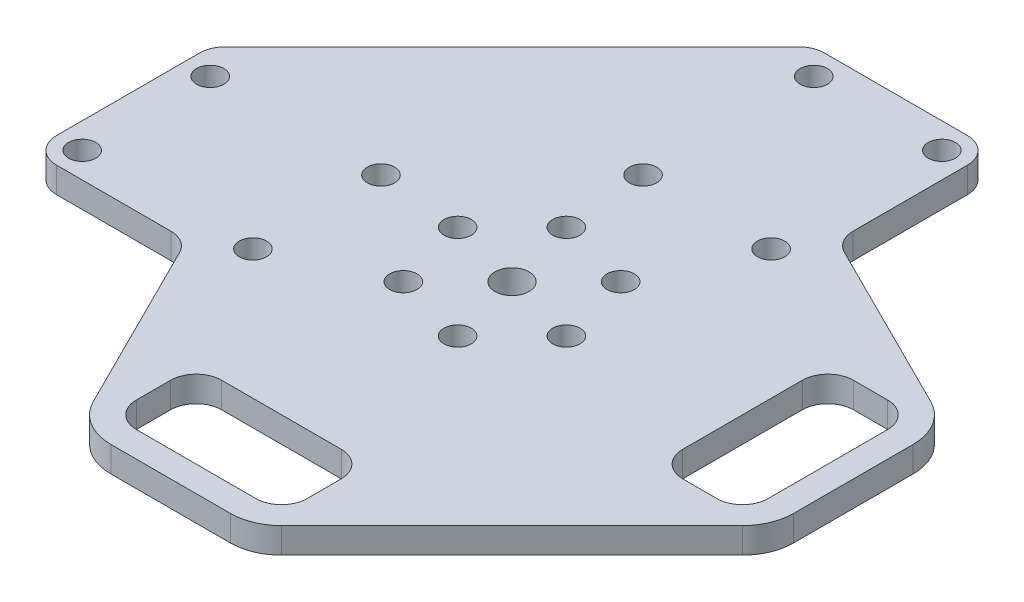
SolidWorks part; units mm, degrees
material "6061-T6 (SS)"
ref_plane "Front Plane" through (0, 0, 0) normal (0, 0, 1) x (1, 0, 0)
ref_plane "Top Plane" through (0, 0, 0) normal (0, 1, 0) x (1, 0, 0)
ref_plane "Right Plane" through (0, 0, 0) normal (1, 0, 0) x (0, 0, -1)
sketch "Sketch1" plane through (0, 0, 0) normal (0, 1, 0) x (1, 0, 0)
  line L1 (11.85, 18.5) -> (-3.15, 18.5)
  line L2 (11.85, 18.5) -> (11.85, 38.5)
  line L3 (11.85, 38.5) -> (-3.15, 38.5)
  line L4 (-3.15, 18.5) -> (-3.15, 38.5)
  line L5 (11.85, 18.5) -> (-3.15, 38.5) construction
  line L6 (11.85, 38.5) -> (-3.15, 18.5) construction
  line L7 (-18.5, -11.85) -> (-38.5, -11.85)
  line L8 (-18.5, -11.85) -> (-18.5, 3.15)
  line L9 (-18.5, 3.15) -> (-38.5, 3.15)
  line L10 (-38.5, -11.85) -> (-38.5, 3.15)
  line L11 (-18.5, -11.85) -> (-38.5, 3.15) construction
  line L12 (-18.5, 3.15) -> (-38.5, -11.85) construction
  line L13 (21.7, 15) -> (-13, 15)
  line L14 (21.7, 15) -> (21.7, 42)
  line L15 (21.7, 42) -> (-13, 42)
  line L16 (-13, 15) -> (-13, 42)
  line L17 (21.7, 15) -> (-13, 42) construction
  line L18 (21.7, 42) -> (-13, 15) construction
  line L19 (-15, -21.7) -> (-42, -21.7)
  line L20 (-15, -21.7) -> (-15, 13)
  line L21 (-15, 13) -> (-42, 13)
  line L22 (-42, -21.7) -> (-42, 13)
  line L23 (-15, -21.7) -> (-42, 13) construction
  line L24 (-15, 13) -> (-42, -21.7) construction
  circle A0 centre (0, 0) radius 2
  circle A1 centre (0, 0) radius 9
  circle A2 centre (0, 0) radius 12.7
  point P3 (4.35, 28.5)
  point P8 (-28.5, -4.35)
  point P16 (-28.5, -4.35)
  point P17 (4.35, 28.5)
  dimension "D1" = 4
  dimension "D4" = 18
  dimension "D11" = 25.4
  dimension "D2" = 20
  dimension "D3" = 15
  dimension "D5" = 34.7
  dimension "D6" = 27
  dimension "D7" = 2
  dimension "D8" = 2
  dimension "D9" = 15
  dimension "D10" = 15
sketch "Sketch2" plane through (0, 0, 0) normal (0, 1, 0) x (1, 0, 0)
  line L0 (-6.15, 41.5) -> (14.85, 41.5)
  line L1 (14.85, 41.5) -> (14.85, 15.5)
  line L3 (-15.5, -14.85) -> (-41.5, -14.85)
  line L4 (-41.5, -14.85) -> (-41.5, 6.15)
  line L5 (-41.5, 6.15) -> (-6.15, 41.5)
  line L6 (-18.5, -11.85) -> (-38.5, -11.85) construction
  line L7 (11.85, 18.5) -> (11.85, 38.5) construction
  line L8 (11.85, 38.5) -> (-3.15, 38.5) construction
  line L9 (-38.5, -11.85) -> (-38.5, 3.15) construction
  line L10 (-18.5, -11.85) -> (-18.5, 3.15) construction
  line L11 (11.85, 18.5) -> (-3.15, 18.5) construction
  line L12 (-18.5, 3.15) -> (-38.5, 3.15) construction
  line L13 (-3.15, 18.5) -> (-3.15, 38.5) construction
  line L14 (-15.5, -14.85) -> (0.9826, -13.6647)
  line L15 (14.85, 15.5) -> (13.6647, -0.9826)
  circle A1 centre (0, 0) radius 12.7 construction
  arc A3 (0.9826, -13.6647) -> (13.6647, -0.9826) centre (0, 0) ccw
  point P11 (0, 0)
  dimension "D1" = 1
  dimension "D2" = 3
  dimension "D3" = 3
  dimension "D4" = 3
  dimension "D5" = 3
  dimension "D6" = 3
  dimension "D7" = 3
  dimension "D8" = 3
  dimension "D9" = 3
extrude "Boss-Extrude1" add sketch "Sketch2" along normal blind 3
hole_wizard "M3 Clearance Hole1" positions "Sketch3" profile "Sketch4" hole size "M3" standard "ANSI Metric" end condition up to next
sketch "Sketch3" plane through (0, 3, 0) normal (0, 1, 0) x (1, 0, 0)
  point P0 (-38.5, 3.15)
  point P3 (-18.5, 3.15)
  point P6 (-18.5, -11.85)
  point P9 (-38.5, -11.85)
  point P12 (-3.15, 18.5)
  point P15 (-3.15, 38.5)
  point P18 (11.85, 38.5)
  point P21 (11.85, 18.5)
sketch "Sketch4" plane through (-38.5, 3, -3.15) normal (1, 0, 0) x (0, 0, 1)
  line L0 (0, 0) -> (0, 3)
  line L1 (0, 3) -> (1.6, 3)
  line L2 (1.6, 3) -> (1.6, 0)
  line L5 (1.6, 0) -> (0, 0)
  line L11 (0, -6.35) -> (0, 107.95) construction
  dimension "Thru Hole Dia." = 3.2
  dimension "Thru Hole Depth" = 3
hole_wizard "M3 Clearance Hole2" positions "Sketch5" profile "Sketch6" hole size "M3" standard "ANSI Metric" end condition up to next
sketch "Sketch5" plane through (0, 3, 0) normal (0, 1, 0) x (1, 0, 0)
  line L4 (-8.6933, 2.3294) -> (-2.3294, 8.6933) construction
  line L5 (0, 0) -> (-5.5114, 5.5114) construction
  line L7 (-1000, 0) -> (49000, 0) construction
  circle A0 centre (0, 0) radius 9 construction
  point P23 (-2.3294, 8.6933)
  point P46 (6.364, 6.364)
  point P47 (8.6933, -2.3294)
  point P48 (2.3294, -8.6933)
  point P49 (-6.364, -6.364)
  point P50 (-8.6933, 2.3294)
  dimension "D1" = 45
  dimension "D2" = 6
sketch "Sketch6" plane through (-2.3294, 3, -8.6933) normal (1, 0, 0) x (0, 0, 1)
  line L0 (0, 0) -> (0, 3)
  line L1 (0, 3) -> (1.6, 3)
  line L2 (1.6, 3) -> (1.6, 0)
  line L5 (1.6, 0) -> (0, 0)
  line L11 (0, -6.35) -> (0, 107.95) construction
  dimension "Thru Hole Dia." = 3.2
  dimension "Thru Hole Depth" = 3
hole_wizard "Ø4.0 (4) Diameter Hole1" positions "Sketch7" profile "Sketch8" hole size "Ø4.0" standard "ANSI Metric" end condition up to next
sketch "Sketch7" plane through (0, 3, 0) normal (0, 1, 0) x (1, 0, 0)
  point P0 (0, 0)
sketch "Sketch8" plane through (0, 3, 0) normal (1, 0, 0) x (0, 0, 1)
  line L0 (0, 0) -> (0, 3)
  line L1 (0, 3) -> (2, 3)
  line L2 (2, 3) -> (2, 0)
  line L5 (2, 0) -> (0, 0)
  line L11 (0, -6.35) -> (0, 107.95) construction
  dimension "Thru Hole Dia." = 4
  dimension "Thru Hole Depth" = 3
ref_plane "Plane1" through (0, 0, 0) normal (-0.7071, 0, 0.7071) x (0.7071, 0, 0.7071)
sketch "Sketch11" plane through (0, 3, 0) normal (0, 1, 0) x (1, 0, 0)
  line L1 (7, -37) -> (-7, -37)
  line L2 (10, -34) -> (10, -30)
  line L3 (7, -27) -> (-7, -27)
  line L4 (-10, -34) -> (-10, -30)
  line L5 (10, -37) -> (-10, -27) construction
  line L6 (10, -27) -> (-10, -37) construction
  arc A0 (7, -37) -> (10, -34) centre (7, -34) ccw
  arc A1 (-7, -37) -> (-10, -34) centre (-7, -34) cw
  arc A2 (10, -30) -> (7, -27) centre (7, -30) ccw
  arc A3 (-7, -27) -> (-10, -30) centre (-7, -30) ccw
  point P0 (0, -32)
  point P17 (0, -28.0355)
  point P19 (0, 0)
  dimension "D1" = 3
  dimension "D2" = 10
  dimension "D3" = 20
  dimension "D4" = 32
extrude "Extrude-Thin1" add sketch "Sketch11" against normal up to surface (3 mm away) separate body thin up to face at (0, 0, 2) thin type one direction wall 3
sketch "Sketch12" plane through (0, 3, 0) normal (0, 1, 0) x (1, 0, 0)
  line L0 (-12.3688, -36.6789) -> (-28.5, -4.35) construction
  line L1 (11.2426, -38.2426) -> (24.7426, -24.7426)
  line L2 (-38.8909, 38.8909) -> (38.8909, -38.8909) construction
  line L5 (24.7426, -24.7426) -> (9.6874, -9.6874)
  line L6 (-41.5, -14.85) -> (-15.5, -14.85) construction
  line L7 (-15.5, -14.85) -> (0.9826, -13.6647) construction
  line L8 (-23.2608, -14.85) -> (-15.5, -14.85)
  line L9 (-15.5, -14.85) -> (0.9826, -13.6647)
  line L10 (-12.3688, -36.6789) -> (-23.2608, -14.85)
  line L15 (13, -34) -> (13, -30)
  line L16 (7, -24) -> (-7, -24)
  line L17 (-13, -30) -> (-13, -34)
  line L18 (-7, -40) -> (7, -40)
  line L19 (13, -34) -> (13, -30)
  line L20 (7, -24) -> (-7, -24)
  line L21 (-13, -30) -> (-13, -34)
  arc A0 (-13, -34) -> (-7, -40) centre (-7, -34) ccw construction
  arc A1 (7, -40) -> (13, -34) centre (7, -34) ccw construction
  arc A4 (0.9826, -13.6647) -> (13.6647, -0.9826) centre (0, 0) ccw construction
  arc A5 (0.9826, -13.6647) -> (9.6874, -9.6874) centre (0, 0) ccw
  arc A10 (7, -40) -> (13, -34) centre (7, -34) ccw
  arc A11 (13, -30) -> (7, -24) centre (7, -30) ccw
  arc A12 (-7, -24) -> (-13, -30) centre (-7, -30) ccw
  arc A13 (-13, -34) -> (-7, -40) centre (-7, -34) ccw
  arc A14 (11.2426, -38.2426) -> (13, -34) centre (7, -34) ccw
  arc A15 (13, -30) -> (7, -24) centre (7, -30) ccw
  arc A16 (-7, -24) -> (-13, -30) centre (-7, -30) ccw
  arc A17 (-13, -34) -> (-12.3688, -36.6789) centre (-7, -34) ccw
  dimension "D1" = 0
extrude "Boss-Extrude4" add sketch "Sketch12" against normal up to surface (3 mm away) up to face at (0, 0, 2)
mirror "Mirror4" about plane through (0, 0, 0) normal (-0.7071, 0, 0.7071) of bodies 108
fillet "Fillet4" radius 3 6 edges at (14.85, 1.5, -41.5) (-6.15, 1.5, -41.5) (-41.5, 1.5, -6.15) (-41.5, 1.5, 14.85) (14.85, 1.5, -23.2608) (-23.2608, 1.5, 14.85)
